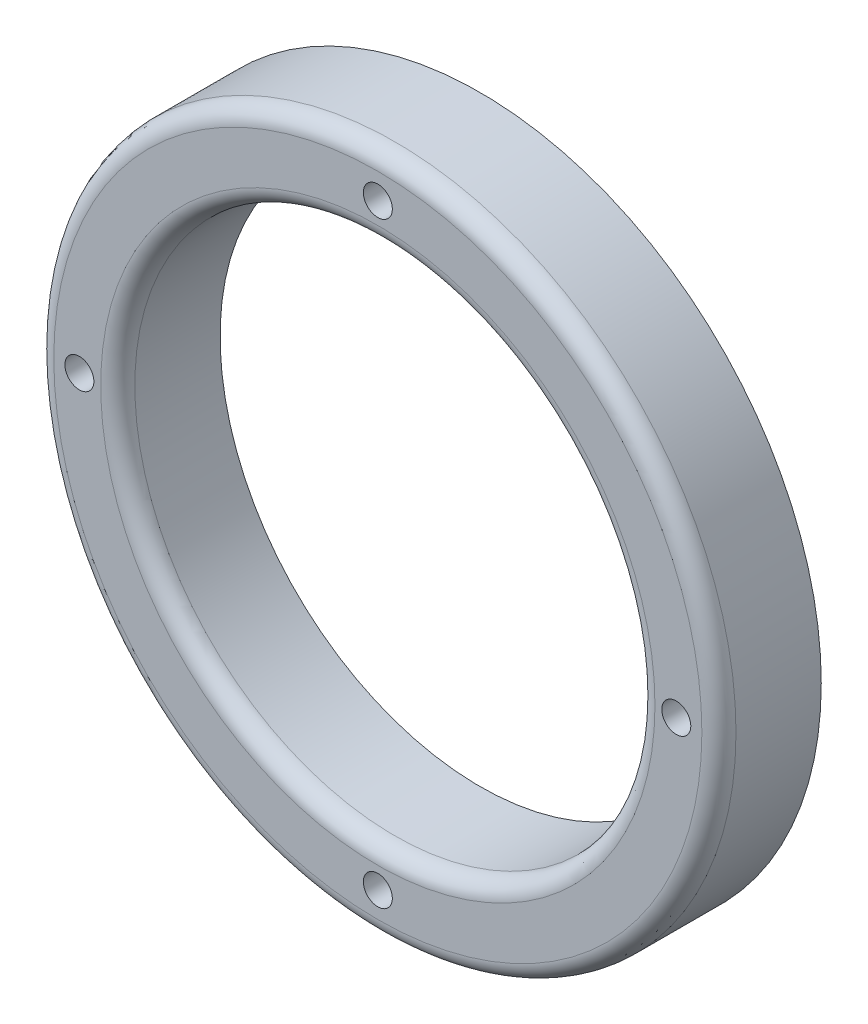
SolidWorks part; units mm, degrees
material "ABS"
ref_plane "前视基准面" through (0, 0, 0) normal (0, 0, 1) x (1, 0, 0)
ref_plane "上视基准面" through (0, 0, 0) normal (0, 1, 0) x (1, 0, 0)
ref_plane "右视基准面" through (0, 0, 0) normal (1, 0, 0) x (0, 0, -1)
sketch "草图1" plane through (0, 0, 0) normal (0, 0, 1) x (1, 0, 0)
  circle A0 centre (0, 0) radius 30.5
  circle A1 centre (0, 0) radius 40
  dimension "D1" = 61
  dimension "D2" = 80
extrude "凸台-拉伸1" add sketch "草图1" along normal blind 12
sketch "草图2" plane through (0, 0, 12) normal (0, 0, 1) x (1, 0, 0)
  line L0 (-40, 0) -> (40, 0) construction
  line L1 (0, 0) -> (0, 40) construction
  circle A0 centre (0, 0) radius 40 construction
  circle A1 centre (35, 0) radius 1.7
  circle A2 centre (0, -35) radius 1.7
  circle A3 centre (-35, 0) radius 1.7
  circle A4 centre (0, 35) radius 1.7
  point P9 (-34.1047, -11.1598)
  point P11 (0, 0)
  point P12 (0, 0)
  point P19 (0, 0)
  dimension "D2" = 3.4
  dimension "D1" = 35
  dimension "D4" = 35
  dimension "D3" = 4
extrude "切除-拉伸1" cut sketch "草图2" against normal blind 12
fillet "圆角1" radius 2 1 edges at (30.5, 0, 12)
fillet "圆角2" radius 2 1 edges at (40, 0, 12)
